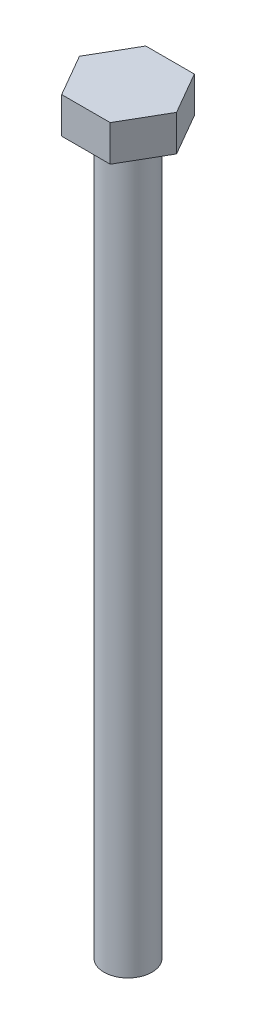
SolidWorks part; units mm, degrees
ref_plane "Front Plane" through (0, 0, 0) normal (0, 0, 1) x (1, 0, 0)
ref_plane "Top Plane" through (0, 0, 0) normal (0, 1, 0) x (1, 0, 0)
ref_plane "Right Plane" through (0, 0, 0) normal (1, 0, 0) x (0, 0, -1)
sketch "Sketch1" plane through (0, 0, 0) normal (0, 1, 0) x (1, 0, 0)
  circle A0 centre (0, 0) radius 2
  dimension "D1" = 4
extrude "Boss-Extrude1" add sketch "Sketch1" along normal blind 60
sketch "Sketch2" plane through (0, 60, 0) normal (0, 1, 0) x (1, 0, 0)
  line L1 (4.0415, 0) -> (2.0207, 3.5)
  line L2 (2.0207, 3.5) -> (-2.0207, 3.5)
  line L3 (-2.0207, 3.5) -> (-4.0415, 0)
  line L4 (-4.0415, 0) -> (-2.0207, -3.5)
  line L5 (-2.0207, -3.5) -> (2.0207, -3.5)
  line L6 (2.0207, -3.5) -> (4.0415, 0)
  circle A0 centre (0, 0) radius 3.5 construction
  dimension "D1" = 7
extrude "Boss-Extrude2" add sketch "Sketch2" along normal blind 3
